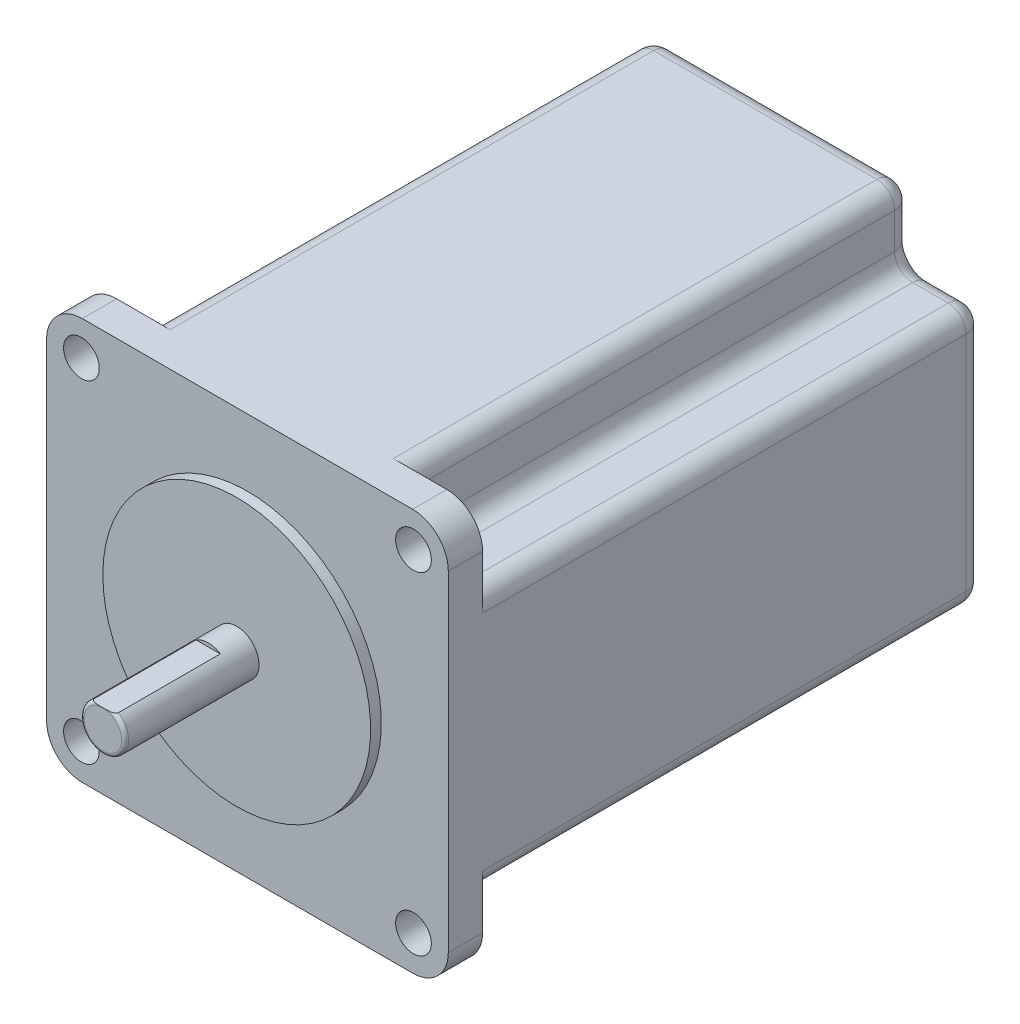
SolidWorks part; units mm, degrees
ref_plane "Front Plane" through (0, 0, 0) normal (0, 0, 1) x (1, 0, 0)
ref_plane "Top Plane" through (0, 0, 0) normal (0, 1, 0) x (1, 0, 0)
ref_plane "Right Plane" through (0, 0, 0) normal (1, 0, 0) x (0, 0, -1)
sketch "Sketch1" plane through (0, 0, 0) normal (0, 0, 1) x (1, 0, 0)
  line L1 (0, 0) -> (57.15, 0)
  line L2 (0, 0) -> (0, 57.15)
  line L3 (0, 57.15) -> (57.15, 57.15)
  line L4 (57.15, 0) -> (57.15, 57.15)
  dimension "D1" = 57.15
  dimension "D2" = 57.15
extrude "Boss-Extrude1" add sketch "Sketch1" along normal blind 76.2
sketch "Sketch2" plane through (0, 0, 76.2) normal (0, 0, 1) x (1, 0, 0)
  line L0 (28.575, 0) -> (28.575, 57.15) construction
  line L1 (0, 0) -> (57.15, 0) construction
  line L2 (57.15, 57.15) -> (0, 57.15) construction
  line L3 (57.15, 28.575) -> (0, 28.575) construction
  line L4 (57.15, 0) -> (57.15, 57.15) construction
  line L5 (0, 57.15) -> (0, 0) construction
  circle A0 centre (28.575, 28.575) radius 19.05
  dimension "D1" = 38.1
extrude "Boss-Extrude2" add sketch "Sketch2" along normal blind 1.524
sketch "Sketch3" plane through (0, 0, 77.724) normal (0, 0, 1) x (1, 0, 0)
  circle A0 centre (28.575, 28.575) radius 3.175
  dimension "D1" = 6.35
extrude "Boss-Extrude3" add sketch "Sketch3" along normal blind 19.05
sketch "Sketch18" plane through (0, 0, 0) normal (0, 0, -1) x (-1, 0, 0)
  line L1 (-10.16, 46.99) -> (10.16, 46.99)
  line L2 (-10.16, 46.99) -> (-10.16, 67.31)
  line L3 (-10.16, 67.31) -> (10.16, 67.31)
  line L4 (10.16, 46.99) -> (10.16, 67.31)
  line L5 (-10.16, 46.99) -> (10.16, 67.31) construction
  line L6 (-10.16, 67.31) -> (10.16, 46.99) construction
  point P0 (0, 57.15)
  dimension "D1" = 20.32
  dimension "D2" = 20.32
extrude "Cut-Extrude13" cut sketch "Sketch18" against normal blind 71.3232
sketch "Sketch20" plane through (0, 0, 0) normal (0, 0, -1) x (-1, 0, 0)
  line L1 (10.16, 10.16) -> (-10.16, 10.16)
  line L2 (10.16, 10.16) -> (10.16, -10.16)
  line L3 (10.16, -10.16) -> (-10.16, -10.16)
  line L4 (-10.16, 10.16) -> (-10.16, -10.16)
  line L5 (10.16, 10.16) -> (-10.16, -10.16) construction
  line L6 (10.16, -10.16) -> (-10.16, 10.16) construction
  point P0 (0, 0)
  dimension "D1" = 20.32
  dimension "D2" = 20.32
extrude "Cut-Extrude14" cut sketch "Sketch20" against normal blind 71.3232
sketch "Sketch21" plane through (0, 0, 0) normal (0, 0, -1) x (-1, 0, 0)
  line L1 (-46.99, 10.16) -> (-67.31, 10.16)
  line L2 (-46.99, 10.16) -> (-46.99, -10.16)
  line L3 (-46.99, -10.16) -> (-67.31, -10.16)
  line L4 (-67.31, 10.16) -> (-67.31, -10.16)
  line L5 (-46.99, 10.16) -> (-67.31, -10.16) construction
  line L6 (-46.99, -10.16) -> (-67.31, 10.16) construction
  point P1 (-57.15, 0)
  dimension "D1" = 20.32
  dimension "D2" = 20.32
extrude "Cut-Extrude15" cut sketch "Sketch21" against normal blind 71.3232
sketch "Sketch22" plane through (0, 0, 0) normal (0, 0, -1) x (-1, 0, 0)
  line L1 (-67.31, 67.31) -> (-46.99, 67.31)
  line L2 (-67.31, 67.31) -> (-67.31, 46.99)
  line L3 (-67.31, 46.99) -> (-46.99, 46.99)
  line L4 (-46.99, 67.31) -> (-46.99, 46.99)
  line L5 (-67.31, 67.31) -> (-46.99, 46.99) construction
  line L6 (-67.31, 46.99) -> (-46.99, 67.31) construction
  point P0 (-57.15, 57.15)
  dimension "D1" = 20.32
  dimension "D2" = 20.32
extrude "Cut-Extrude16" cut sketch "Sketch22" against normal blind 71.3232
sketch "Sketch11" plane through (0, 0, 76.2) normal (0, 0, 1) x (1, 0, 0)
  line L0 (4.953, 57.15) -> (4.953, 52.2331) construction
  line L1 (57.15, 57.15) -> (0, 57.15) construction
  line L2 (4.953, 52.2331) -> (0, 52.2331) construction
  line L3 (0, 57.15) -> (0, 0) construction
  circle A0 centre (4.953, 52.2331) radius 2.54
  dimension "D1" = 5.08
extrude "Cut-Extrude8" cut sketch "Sketch11" against normal through all
sketch "Sketch12" plane through (0, 0, 76.2) normal (0, 0, 1) x (1, 0, 0)
  line L0 (4.953, 52.2331) -> (52.197, 52.2331) construction
  circle A0 centre (52.197, 52.2331) radius 2.54
  dimension "D2" = 5.08
  dimension "D1" = 47.244
extrude "Cut-Extrude9" cut sketch "Sketch12" against normal through all
sketch "Sketch14" plane through (0, 0, 76.2) normal (0, 0, 1) x (1, 0, 0)
  line L0 (4.953, 52.2331) -> (4.953, 4.9891) construction
  line L1 (4.953, 4.9891) -> (52.197, 4.9891) construction
  circle A0 centre (4.953, 4.9891) radius 2.54
  dimension "D3" = 5.08
  dimension "D1" = 47.244
  dimension "D2" = 47.244
extrude "Cut-Extrude10" cut sketch "Sketch14" against normal through all
sketch "Sketch15" plane through (0, 0, 76.2) normal (0, 0, 1) x (1, 0, 0)
  line L0 (4.953, 4.9891) -> (52.197, 4.9891) construction
  line L1 (52.197, 52.2331) -> (52.197, 4.9891) construction
  circle A0 centre (52.197, 4.9891) radius 2.54
  dimension "D2" = 5.08
  dimension "D1" = 47.244
extrude "Cut-Extrude11" cut sketch "Sketch15" against normal through all
fillet "Fillet2" radius 5.08 4 edges at (57.15, 57.15, 73.7616) (57.15, 0, 73.7616) (0, 0, 73.7616) (0, 57.15, 73.7616)
fillet "Fillet4" radius 2.54 24 edges at (28.575, 57.15, 0) (0, 28.575, 0) (28.575, 0, 0) (57.15, 28.575, 0) (10.16, 52.07, 0) (5.08, 46.99, 0) (5.08, 10.16, 0) (10.16, 5.08, 0) (46.99, 5.08, 0) (52.07, 10.16, 0) (52.07, 46.99, 0) (46.99, 52.07, 0) (0, 46.99, 35.6616) (10.16, 46.99, 35.6616) (10.16, 57.15, 35.6616) (46.99, 57.15, 35.6616) (46.99, 46.99, 35.6616) (57.15, 46.99, 35.6616) (57.15, 10.16, 35.6616) (46.99, 10.16, 35.6616) (46.99, 0, 35.6616) (10.16, 0, 35.6616) (0, 10.16, 35.6616) (10.16, 10.16, 35.6616)
fillet "Fillet1" radius 0.508 1 edges at (31.75, 28.575, 96.774)
sketch "Sketch10" plane through (0, 0, 96.774) normal (0, 0, 1) x (1, 0, 0)
  line L0 (28.575, 25.4) -> (28.575, 31.242) construction
  line L2 (25.4566, 32.3482) -> (32.6055, 32.3482)
  line L3 (25.4566, 32.3482) -> (25.4566, 31.242)
  line L4 (25.4566, 31.242) -> (32.6055, 31.242)
  line L5 (32.6055, 32.3482) -> (32.6055, 31.242)
  circle A0 centre (28.575, 28.575) radius 3.175 construction
  circle A1 centre (28.575, 28.575) radius 3.175 construction
  dimension "D1" = 5.842
extrude "Cut-Extrude7" cut sketch "Sketch10" against normal blind 14.986
sketch "Sketch23" plane through (0, 0, 0) normal (0, -1, 0) x (1, 0, 0)
  line L0 (12.7, 71.3232) -> (12.7, 2.54) construction
  circle A0 centre (28.575, 7.3438) radius 3.429
  dimension "D2" = 6.858
  dimension "D1" = 15.875
extrude "Wire" add sketch "Sketch23" along normal blind 5.842
